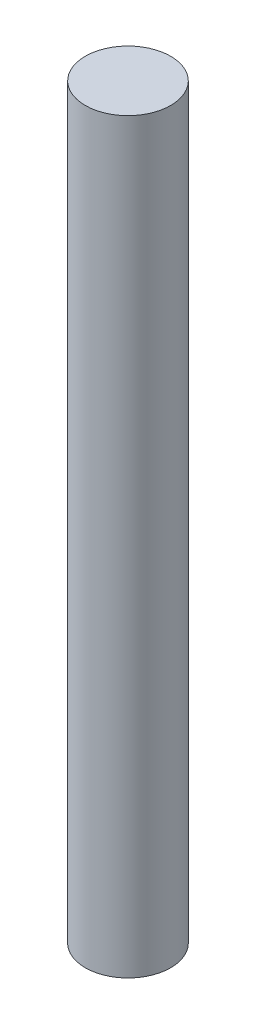
SolidWorks part; units mm, degrees
ref_plane "前视基准面" through (0, 0, 0) normal (0, 0, 1) x (1, 0, 0)
ref_plane "上视基准面" through (0, 0, 0) normal (0, 1, 0) x (1, 0, 0)
ref_plane "右视基准面" through (0, 0, 0) normal (1, 0, 0) x (0, 0, -1)
sketch "草图1" plane through (0, 0, 0) normal (0, 1, 0) x (1, 0, 0)
  circle A0 centre (0, 0) radius 4
extrude "凸台-拉伸1" add sketch "草图1" along normal blind 70
